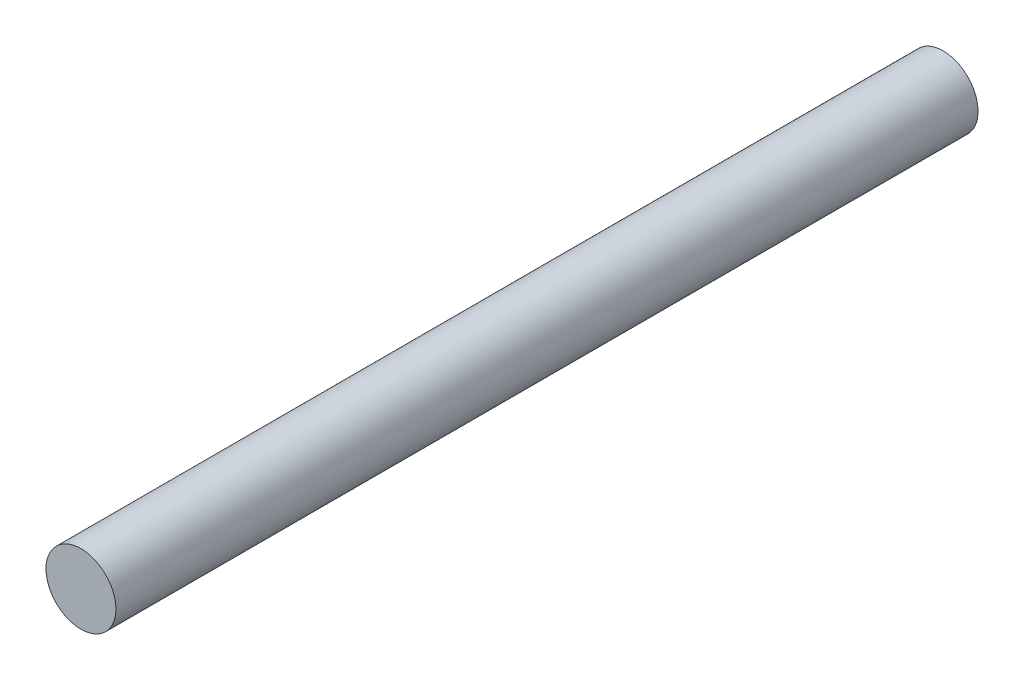
SolidWorks part; units mm, degrees
ref_plane "Plan de face" through (0, 0, 0) normal (0, 0, 1) x (1, 0, 0)
ref_plane "Plan de dessus" through (0, 0, 0) normal (0, 1, 0) x (1, 0, 0)
ref_plane "Plan de droite" through (0, 0, 0) normal (1, 0, 0) x (0, 0, -1)
sketch "Esquisse2" plane through (0, 0, 0) normal (0, 0, 1) x (1, 0, 0)
  circle A0 centre (0, 0) radius 49.403
  dimension "D1" = 98.806
extrude "Boss.-Extru.1" add sketch "Esquisse2" along normal blind 1219.2
